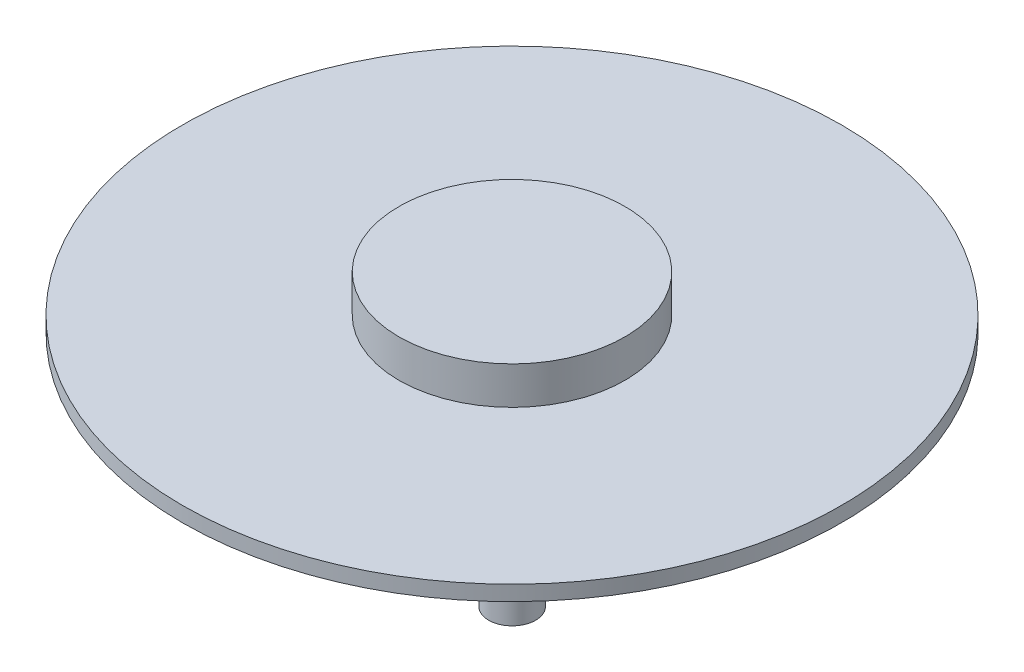
SolidWorks part; units mm, degrees
ref_plane "Front Plane" through (0, 0, 0) normal (0, 0, 1) x (1, 0, 0)
ref_plane "Top Plane" through (0, 0, 0) normal (0, 1, 0) x (1, 0, 0)
ref_plane "Right Plane" through (0, 0, 0) normal (1, 0, 0) x (0, 0, -1)
sketch "SK_P01_Standoff" plane through (0, 0, 0) normal (0, 1, 0) x (1, 0, 0)
  circle A0 centre (21.222, -21.205) radius 2.5
extrude "P01_Standoff" add sketch "SK_P01_Standoff" along normal blind 4
sketch "SK_P02_Standoff" plane through (0, 0, 0) normal (0, 1, 0) x (1, 0, 0)
  circle A0 centre (-21.209, -21.217) radius 2.5
extrude "P02_Standoff" add sketch "SK_P02_Standoff" along normal blind 4
sketch "SK_P03_Standoff" plane through (0, 0, 0) normal (0, 1, 0) x (1, 0, 0)
  circle A0 centre (-21.213, 21.213) radius 2.5
extrude "P03_Standoff" add sketch "SK_P03_Standoff" along normal blind 4
sketch "SK_P04_Standoff" plane through (0, 0, 0) normal (0, 1, 0) x (1, 0, 0)
  circle A0 centre (21.218, 21.209) radius 2.5
extrude "P04_Standoff" add sketch "SK_P04_Standoff" along normal blind 4
sketch "SK_P05_Micarrayboard70mm" plane through (0, 0, 0) normal (0, 1, 0) x (1, 0, 0)
  circle A0 centre (0, 0) radius 35
extrude "P05_Micarrayboard70mm" add sketch "SK_P05_Micarrayboard70mm" along normal blind 1.6 from offset 4
sketch "SK_P06_DSPandLEDs" plane through (0, 0, 0) normal (0, 1, 0) x (1, 0, 0)
  circle A0 centre (0, 0) radius 12
extrude "P06_DSPandLEDs" add sketch "SK_P06_DSPandLEDs" along normal blind 4 from offset 5.6
